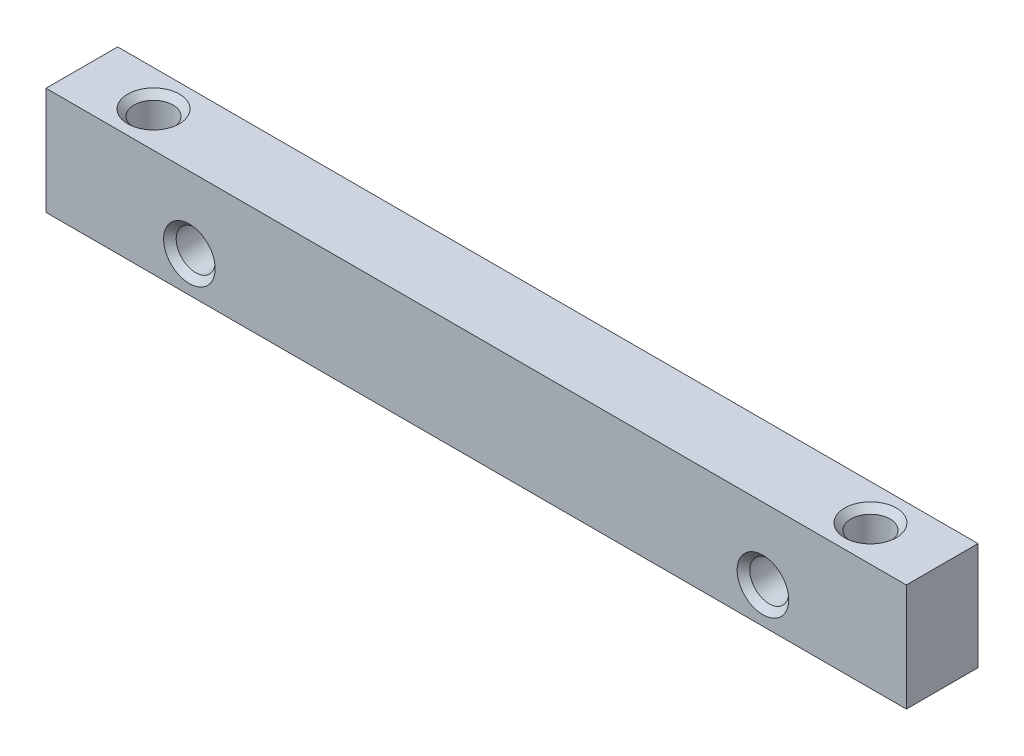
SolidWorks part; units mm, degrees
material "ASTM A36 Steel"
ref_plane "Front Plane" through (0, 0, 0) normal (0, 0, 1) x (1, 0, 0)
ref_plane "Top Plane" through (0, 0, 0) normal (0, 1, 0) x (1, 0, 0)
ref_plane "Right Plane" through (0, 0, 0) normal (1, 0, 0) x (0, 0, -1)
sketch "Sketch1" plane through (0, 0, 0) normal (1, 0, 0) x (0, 0, -1)
  line L1 (-3.175, 4.7625) -> (3.175, 4.7625)
  line L2 (-3.175, 4.7625) -> (-3.175, -4.7625)
  line L3 (-3.175, -4.7625) -> (3.175, -4.7625)
  line L4 (3.175, 4.7625) -> (3.175, -4.7625)
  point P4 (3.175, 0)
  point P5 (0, 4.7625)
  dimension "D1" = 9.525
  dimension "D2" = 6.35
extrude "Boss-Extrude1" add sketch "Sketch1" along normal mid plane 76.2
hole_wizard "#8-32 Tapped Hole1" positions "Sketch3" profile "Sketch2" tap size "#8-32" standard "Ansi Inch" end condition through all
sketch "Sketch3" plane through (0, 4.7625, 0) normal (0, 1, 0) x (-1, 0, 0)
  point P0 (-31.75, 0)
  point P1 (31.75, 0)
  dimension "D1" = 31.75
  dimension "D2" = 31.75
sketch "Sketch2" plane through (31.75, 4.7625, 0) normal (1, 0, 0) x (0, 0, 1)
  line L0 (0, 0) -> (0, 9.525)
  line L1 (0, 9.525) -> (2.286, 9.525)
  line L2 (1.7272, 8.9662) -> (1.7272, 0.5588)
  line L3 (1.7272, 0.5588) -> (2.286, 0)
  line L5 (2.286, 0) -> (0, 0)
  line L6 (-1.7272, 0.5588) -> (-2.286, 0) construction
  line L7 (2.286, 9.525) -> (1.7272, 8.9662)
  line L8 (-2.286, 9.525) -> (-1.7272, 8.9662) construction
  line L11 (0, -6.35) -> (0, 107.95) construction
  dimension "Thread Major Dia." = 3.4544
  dimension "Thru Tap Drill Depth" = 9.525
  dimension "Near C'Sink Dia." = 4.572
  dimension "Near C'Sink Angle" = 90
  dimension "Far C'Sink Dia." = 4.572
  dimension "Far C'Sink Angle" = 90
hole_wizard "#8-32 Tapped Hole2" positions "Sketch5" profile "Sketch4" tap size "#8-32" standard "Ansi Inch" end condition up to next
sketch "Sketch5" plane through (0, 0, 3.175) normal (0, 0, 1) x (1, 0, 0)
  point P0 (25.4, -1.5875)
  point P2 (-25.4, -1.5875)
  dimension "D1" = 1.5875
  dimension "D2" = 25.4
  dimension "D3" = 25.4
sketch "Sketch4" plane through (25.4, -1.5875, 3.175) normal (1, 0, 0) x (0, -1, 0)
  line L0 (0, 0) -> (0, 6.35)
  line L1 (0, 6.35) -> (2.286, 6.35)
  line L2 (1.7272, 5.7912) -> (1.7272, 0.5588)
  line L3 (1.7272, 0.5588) -> (2.286, 0)
  line L5 (2.286, 0) -> (0, 0)
  line L6 (-1.7272, 0.5588) -> (-2.286, 0) construction
  line L7 (2.286, 6.35) -> (1.7272, 5.7912)
  line L8 (-2.286, 6.35) -> (-1.7272, 5.7912) construction
  line L11 (0, -6.35) -> (0, 107.95) construction
  dimension "Thread Major Dia." = 3.4544
  dimension "Thru Tap Drill Depth" = 6.35
  dimension "Near C'Sink Dia." = 4.572
  dimension "Near C'Sink Angle" = 90
  dimension "Far C'Sink Dia." = 4.572
  dimension "Far C'Sink Angle" = 90
sketch "Sketch6" plane through (0, 0, 0) normal (0, 0, 1) x (1, 0, 0)
  line L1 (-7.9375, 16.93) -> (7.9375, 16.93)
  line L2 (-7.9375, 16.93) -> (-7.9375, 2.4257)
  line L3 (-7.9375, 2.4257) -> (7.9375, 2.4257)
  line L4 (7.9375, 16.93) -> (7.9375, 2.4257)
  dimension "D1" = 7.9375
  dimension "D2" = 15.875
  dimension "D3" = 2.3368
extrude "Cut-Extrude1" [suppressed] cut sketch "Sketch6" against normal mid plane 12.7
chamfer "Chamfer1" [suppressed] distance 0.762 angle 45
pattern_linear "LPattern1" [suppressed] count 2 spacing 228.6
